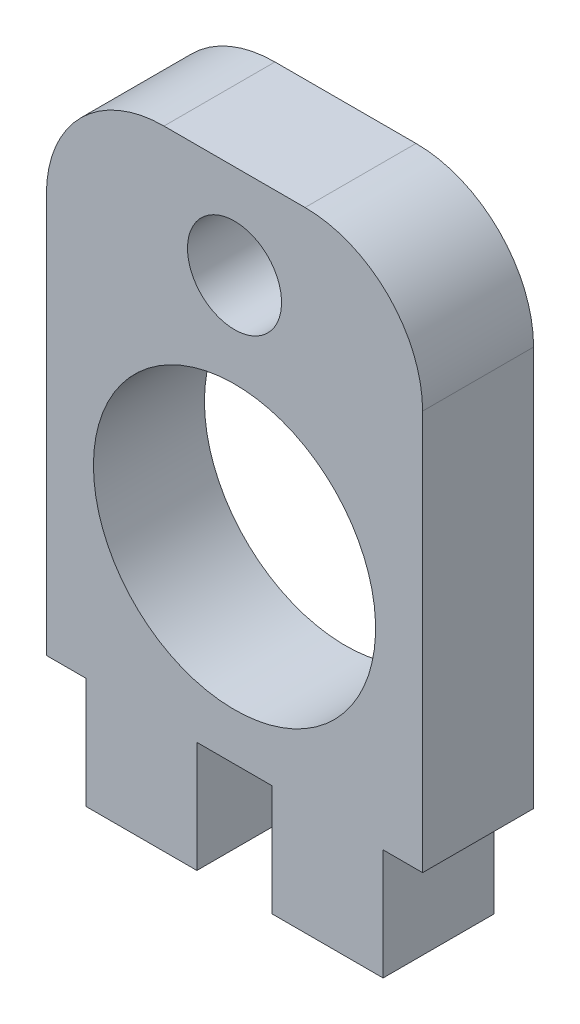
SolidWorks part; units mm, degrees
material "Acrylic (Medium-high impact)"
ref_plane "Front Plane" through (0, 0, 0) normal (0, 0, 1) x (1, 0, 0)
ref_plane "Top Plane" through (0, 0, 0) normal (0, 1, 0) x (1, 0, 0)
ref_plane "Right Plane" through (0, 0, 0) normal (1, 0, 0) x (0, 0, -1)
sketch "Sketch1" plane through (0, 0, 0) normal (0, 0, 1) x (1, 0, 0)
  line L0 (0, 0) -> (1.0668, 0)
  line L1 (1.0668, 0) -> (1.0668, -2.9972)
  line L2 (1.0668, -2.9972) -> (4.064, -2.9972)
  line L3 (4.064, -2.9972) -> (4.064, 0)
  line L4 (4.064, 0) -> (6.096, 0)
  line L5 (6.096, 0) -> (6.096, -2.9972)
  line L6 (6.096, -2.9972) -> (9.0932, -2.9972)
  line L7 (9.0932, -2.9972) -> (9.0932, 0)
  line L8 (9.0932, 0) -> (10.16, 0)
  line L9 (10.16, 0) -> (10.16, 13.97)
  line L10 (10.16, 13.97) -> (0, 13.97)
  line L11 (0, 13.97) -> (0, 0)
  line L12 (5.08, 0) -> (5.08, 13.97) construction
  circle A0 centre (5.08, 5.08) radius 3.81
  circle A1 centre (5.08, 11.43) radius 1.27
  dimension "D4" = 10.16
  dimension "D5" = 7.62
  dimension "D6" = 2.54
  dimension "D1" = 2.9972
  dimension "D2" = 2.032
  dimension "D3" = 13.97
  dimension "D7" = 5.08
  dimension "D8" = 6.35
extrude "Boss-Extrude1" add sketch "Sketch1" along normal blind 2.9972
fillet "Fillet1" radius 3.175 2 edges at (0, 13.97, 1.4986) (10.16, 13.97, 1.4986)
